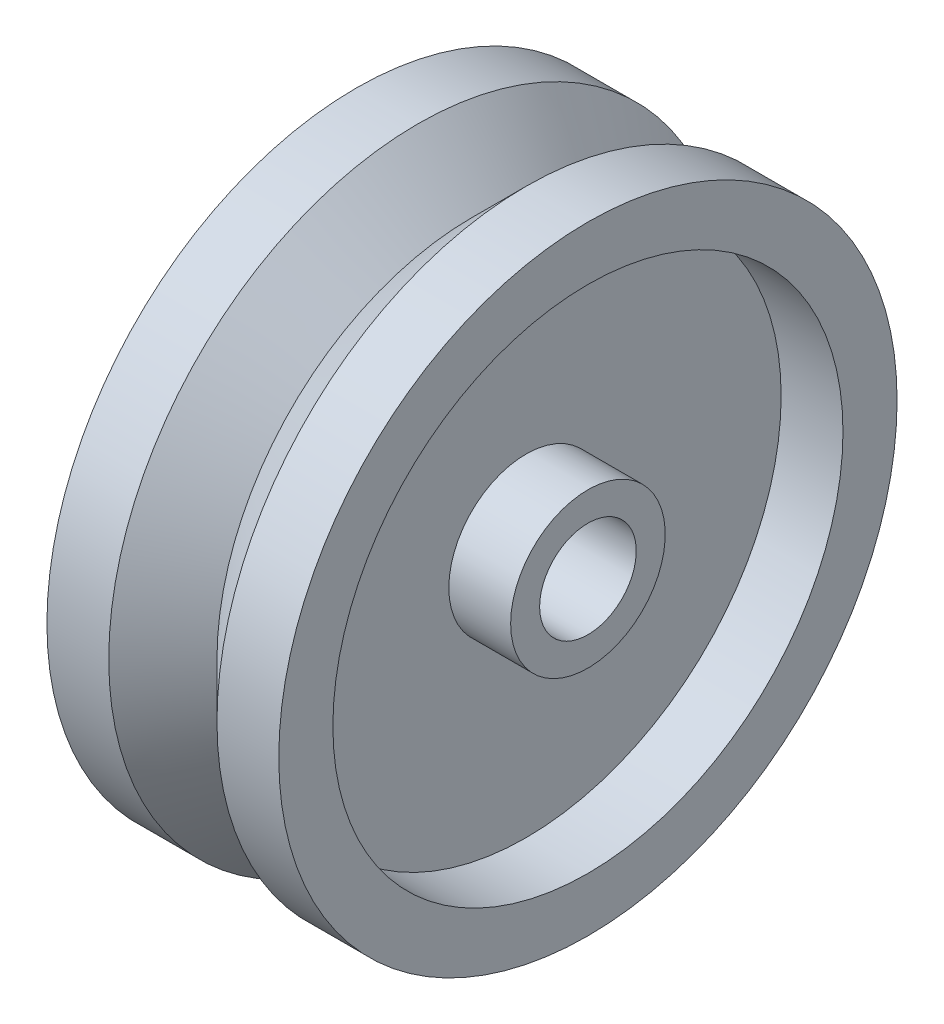
SolidWorks part; units mm, degrees
ref_plane "Front Plane" through (0, 0, 0) normal (0, 0, 1) x (1, 0, 0)
ref_plane "Top Plane" through (0, 0, 0) normal (0, 1, 0) x (1, 0, 0)
ref_plane "Right Plane" through (0, 0, 0) normal (1, 0, 0) x (0, 0, -1)
sketch "Sketch1" plane through (0, 0, 0) normal (0, 0, 1) x (1, 0, 0)
  line L0 (-49.1418, 0) -> (49.1418, 0) construction
  line L1 (-7.5, 20) -> (-3.5, 20)
  line L2 (-7.5, 20) -> (-7.5, 3.125)
  line L4 (7.5, 20) -> (7.5, 3.125)
  line L5 (-7.5, 20) -> (0, 0) construction
  line L6 (3.5, 20) -> (7.5, 20)
  line L7 (-7.5, 3.125) -> (7.5, 3.125)
  line L11 (-7.5, 3.125) -> (0, 0) construction
  line L12 (0, 0) -> (7.5, 3.125) construction
  line L13 (-7.5, 5) -> (-3.5, 5)
  line L14 (-7.5, 5) -> (-7.5, 3.125)
  line L16 (7.5, 5) -> (7.5, 3.125)
  line L17 (-7.5, 5) -> (0, 0) construction
  line L18 (0, 20) -> (0, 41.5589) construction
  line L19 (-7.5, 16.5) -> (-3.5, 16.5)
  line L20 (-7.5, 16.5) -> (-7.5, 3.125)
  line L22 (7.5, 16.5) -> (7.5, 3.125)
  line L23 (-7.5, 16.5) -> (0, 0) construction
  line L24 (7.5, 5) -> (3.5, 5)
  line L25 (3.5, 16.5) -> (3.5, 5)
  line L26 (-3.5, 20) -> (0, 16.5)
  line L27 (0, 16.5) -> (3.5, 20)
  line L29 (-3.5, 16.5) -> (-3.5, 5)
  line L30 (-3.5, 5) -> (-7.5, 5)
  line L31 (7.5, 16.5) -> (3.5, 16.5)
  line L34 (0, 0) -> (7.5, 5) construction
  line L35 (0, 0) -> (7.5, 16.5) construction
  line L36 (0, 0) -> (7.5, 20) construction
  line L37 (0, 0) -> (0, 16.5) construction
  point P0 (0, 0)
  point P6 (0, 0)
  point P11 (0, 0)
  point P16 (0, 0)
  point P24 (0, 0)
  point P27 (0, 0)
  dimension "D6" = 4
revolve "Revolve1" add sketch "Sketch1" angle 360 about L0
